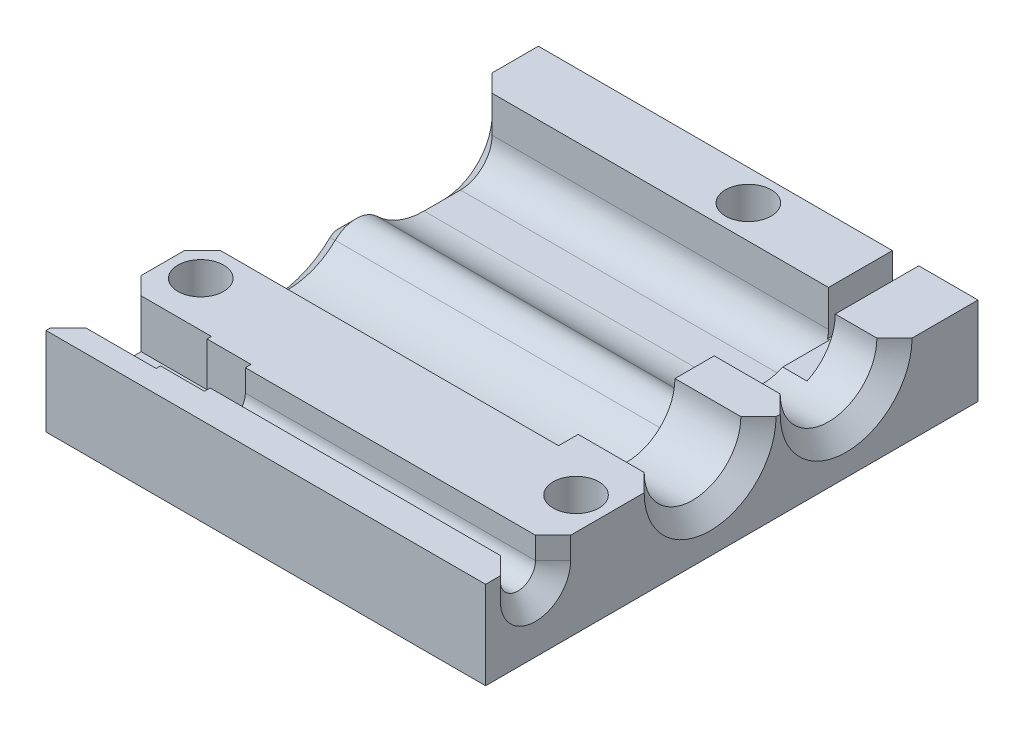
SolidWorks part; units mm, degrees
material "POM Acetal Copolymer"
ref_plane "Front Plane" through (0, 0, 0) normal (0, 0, 1) x (1, 0, 0)
ref_plane "Top Plane" through (0, 0, 0) normal (0, 1, 0) x (1, 0, 0)
ref_plane "Right Plane" through (0, 0, 0) normal (1, 0, 0) x (0, 0, -1)
sketch "Sketch1" plane through (0, 0, 0) normal (0, 1, 0) x (1, 0, 0)
  line L0 (-25, 28) -> (-25, -28)
  line L1 (-25, 28) -> (25, 28)
  line L2 (-25, -28) -> (25, -28)
  line L3 (25, 28) -> (25, -28)
  line L4 (-25, 28) -> (25, -28) construction
  line L5 (-25, -28) -> (25, 28) construction
  point P1 (0, 0)
  dimension "D1" = 50
  dimension "D2" = 56
extrude "Boss-Extrude1" add sketch "Sketch1" along normal blind 10
sketch "Sketch2" plane through (-25, 0, 0) normal (-1, 0, 0) x (0, 0, 1)
  line L1 (-28, 10) -> (28, 10) construction
  circle A0 centre (-13, 10) radius 5.5
  circle A1 centre (2.4688, 10) radius 5.5
  dimension "D2" = 11
  dimension "D4" = 15.4688
  dimension "D5" = 15
extrude "Cut-Extrude1" cut sketch "Sketch2" against normal through all
sketch "Sketch3" plane through (-25, 0, 0) normal (-1, 0, 0) x (0, 0, 1)
  line L0 (-20.7362, 16.8073) -> (-20.7362, 2.265)
  line L1 (-20.7362, 2.265) -> (-13.0012, 2.265)
  line L2 (-28, 10) -> (-18.5, 10) construction
  line L4 (-20.7362, 16.8073) -> (-1.2041, 16.8073)
  arc A0 (-3.0312, 10) -> (7.9688, 10) centre (2.4688, 10) ccw construction
  arc A1 (-2.8995, 4.4312) -> (-1.2041, 16.8073) centre (2.4688, 10) ccw
  arc A2 (-13.0012, 2.265) -> (-7.6328, 4.4312) centre (-13.0012, 10) ccw
  arc A3 (-7.6328, 4.4312) -> (-2.8995, 4.4312) centre (-5.2662, 1.9762) cw
  dimension "D1" = 3.41
  dimension "D2" = 7.735
  dimension "D3" = 15.47
  dimension "D4" = 14.5423
  dimension "D5" = 23.205
extrude "Cut-Extrude2" cut sketch "Sketch3" against normal blind 40.5
fillet "Fillet1" radius 3.6 1 edges at (-4.75, 2.265, -20.7362)
hole_wizard "Ø5.2 (5.2) Diameter Hole1" positions "Sketch5" profile "Sketch4" hole size "Ø5.2" standard "ISO" end condition through all
sketch "Sketch5" plane through (0, 10, 0) normal (0, 1, 0) x (1, 0, 0)
  line L8 (2.378, 24.5) -> (2.378, -14.0592) construction
  line L10 (21.343, -14.0592) -> (-21.343, -14.0592) construction
  line L12 (21.343, -14.0592) -> (25, -14.0592) construction
  line L13 (25, -28) -> (25, -7.9688) construction
  line L16 (-25, -10.2038) -> (-25, -28) construction
  line L17 (-25, -14.0592) -> (-21.343, -14.0592) construction
  line L19 (25, 28) -> (-25, 28) construction
  point P0 (2.378, 24.5)
  point P4 (21.343, -14.0592)
  point P6 (-21.343, -14.0592)
  dimension "D1" = 42.6859
  dimension "D2" = 38.5592
  dimension "D3" = 23.721
  dimension "D4" = 3.5
sketch "Sketch4" plane through (2.378, 10, -24.5) normal (1, 0, 0) x (0, 0, 1)
  line L0 (0, 0) -> (0, 10)
  line L1 (0, 10) -> (2.6, 10)
  line L2 (2.6, 10) -> (2.6, 0)
  line L5 (2.6, 0) -> (0, 0)
  line L11 (0, -6.35) -> (0, 107.95) construction
  dimension "Thru Hole Dia." = 5.2
  dimension "Thru Hole Depth" = 10
sketch "Sketch7" plane through (0, 10, 0) normal (0, 1, 0) x (1, 0, 0)
  line L1 (18.262, 12.6977) -> (15.262, 12.6977)
  line L2 (18.262, 12.6977) -> (18.262, 42.5657)
  line L3 (18.262, 42.5657) -> (15.262, 42.5657)
  line L4 (15.262, 12.6977) -> (15.262, 42.5657)
  line L6 (-25, 28) -> (-25, 20.7362) construction
  dimension "D1" = 3
  dimension "D2" = 40.262
extrude "Cut-Extrude3" cut sketch "Sketch7" against normal blind 5
sketch "Sketch8" plane through (-25, 0, 0) normal (-1, 0, 0) x (0, 0, 1)
  line L0 (19.6796, 15) -> (19.6796, 5)
  line L1 (19.6796, 15) -> (24.9796, 15)
  line L2 (19.6796, 5) -> (24.9796, 5)
  line L3 (24.9796, 15) -> (24.9796, 5)
  line L4 (19.6796, 15) -> (24.9796, 5) construction
  line L5 (19.6796, 5) -> (24.9796, 15) construction
  line L6 (16.6592, 10) -> (28, 10) construction
  line L7 (10.2038, 10) -> (28, 10) construction
  point P1 (22.3296, 10)
  dimension "D1" = 5.3
  dimension "D2" = 10
extrude "Cut-Extrude4" cut sketch "Sketch8" against normal blind 15
sketch "Sketch9" plane through (-10, 0, 0) normal (-1, 0, 0) x (0, 0, 1)
  line L0 (22.3296, 12.5) -> (22.3296, 7.5) construction
  line L1 (19.6796, 10) -> (24.9796, 10) construction
  line L2 (24.3296, 12.5) -> (24.3296, 7.5)
  line L3 (20.3296, 12.5) -> (20.3296, 7.5)
  arc A0 (24.3296, 12.5) -> (20.3296, 12.5) centre (22.3296, 12.5) ccw
  arc A1 (20.3296, 7.5) -> (24.3296, 7.5) centre (22.3296, 7.5) ccw
  point P4 (22.3296, 10)
  dimension "D1" = 2
  dimension "D2" = 5
extrude "Cut-Extrude5" cut sketch "Sketch9" against normal through all
sketch "Sketch10" plane through (-25, 0, 0) normal (-1, 0, 0) x (0, 0, 1)
  line L0 (19.1796, 15.5) -> (19.1796, 4.5)
  line L1 (19.1796, 4.5) -> (25.4796, 4.5)
  line L2 (25.4796, 4.5) -> (25.4796, 15.5)
  line L3 (25.4796, 15.5) -> (19.1796, 15.5)
  line L4 (19.6796, 15) -> (19.6796, 5)
  line L5 (19.6796, 5) -> (24.9796, 5)
  line L6 (24.9796, 5) -> (24.9796, 15)
  line L7 (24.9796, 15) -> (19.6796, 15)
  line L8 (19.6796, 15) -> (19.6796, 5) construction
  line L9 (19.6796, 5) -> (24.9796, 5) construction
  line L10 (24.9796, 5) -> (24.9796, 15) construction
  line L11 (24.9796, 15) -> (19.6796, 15) construction
  dimension "D1" = 0
  dimension "D2" = 0.5
extrude "Cut-Extrude6" cut sketch "Sketch10" against normal blind 10
chamfer "Chamfer1" distance 2 angle 45 9 edges at (-25, 7.9325, -20.7362) (-25, 3.3194, -19.6817) (-25, 2.8812, 5.4942) (-25, 2.265, -15.0687) (-25, 5.3862, -5.2662) (-25, 2.827, -10.1067) (-25, 7.25, 25.4796) (-25, 7.25, 19.1796) (-25, 4.5, 22.3296)
chamfer "Chamfer2" distance 2 angle 45 5 edges at (25, 4.5, 2.4688) (25, 4.5, -13) (25, 8.75, 20.3296) (25, 8.75, 24.3296) (25, 5.5, 22.3296)
sketch "Sketch12" plane through (0, 5, 0) normal (0, 1, 0) x (1, 0, 0)
  line L0 (-11.75, -22.3296) -> (-13.25, -22.3296)
  line L1 (-10, -19.6796) -> (-15, -24.9796) construction
  line L2 (-12.5, -21.5796) -> (-12.5, -23.0796)
  point P2 (-12.5, -22.3296)
  dimension "D1" = 1.5
extrude "Cut-Extrude-Thin1" cut sketch "Sketch12" against normal blind 0.5 thin thin type mid plane wall 0.75
